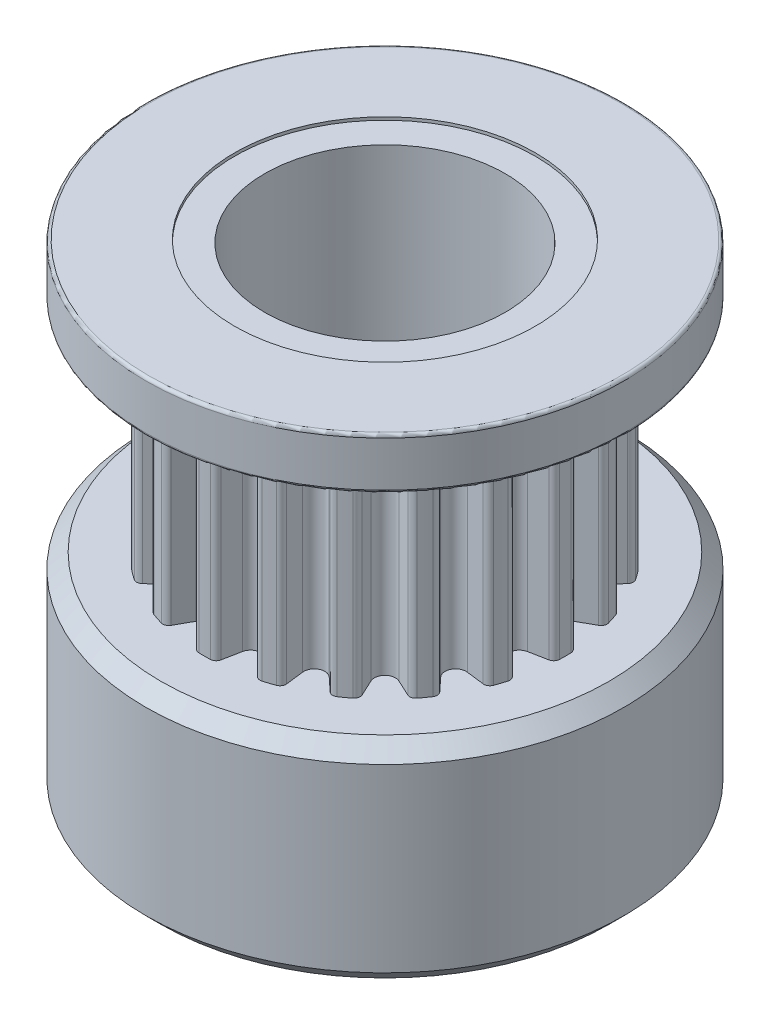
SolidWorks part; units mm, degrees
material "AISI 304"
ref_plane "Front Plane" through (0, 0, 0) normal (0, 0, 1) x (1, 0, 0)
ref_plane "Top Plane" through (0, 0, 0) normal (0, 1, 0) x (1, 0, 0)
ref_plane "Right Plane" through (0, 0, 0) normal (1, 0, 0) x (0, 0, -1)
sketch "Sketch1" plane through (0, 0, 0) normal (0, 1, 0) x (1, 0, 0)
  circle A0 centre (0, 0) radius 7.95
  dimension "D1" = 15.9
extrude "Boss-Extrude1" add sketch "Sketch1" along normal blind 7
sketch "Sketch2" plane through (0, 7, 0) normal (0, 1, 0) x (1, 0, 0)
  line L0 (0, 8.8295) -> (0, -9.5305) construction
  line L1 (-12.1222, 0) -> (11.146, 0) construction
  line L2 (-0.3802, 5.8356) -> (-0.4971, 5.2396)
  line L3 (0.3802, 5.8356) -> (0.4971, 5.2396)
  line L4 (2.1649, 5.4324) -> (2.0919, 4.8296)
  line L5 (1.4417, 5.6674) -> (1.1464, 5.1368)
  line L6 (3.7377, 4.4976) -> (3.4819, 3.9468)
  line L7 (3.1224, 4.9446) -> (2.6776, 4.5311)
  line L8 (4.9446, 3.1224) -> (4.5311, 2.6776)
  line L9 (4.4976, 3.7377) -> (3.9468, 3.4819)
  line L10 (5.6674, 1.4417) -> (5.1368, 1.1464)
  line L11 (5.4324, 2.1649) -> (4.8296, 2.0919)
  line L12 (5.8356, -0.3802) -> (5.2396, -0.4971)
  line L13 (5.8356, 0.3802) -> (5.2396, 0.4971)
  line L14 (5.4324, -2.1649) -> (4.8296, -2.0919)
  line L15 (5.6674, -1.4417) -> (5.1368, -1.1464)
  line L16 (4.4976, -3.7377) -> (3.9468, -3.4819)
  line L17 (4.9446, -3.1224) -> (4.5311, -2.6776)
  line L18 (3.1224, -4.9446) -> (2.6776, -4.5311)
  line L19 (3.7377, -4.4976) -> (3.4819, -3.9468)
  line L20 (1.4417, -5.6674) -> (1.1464, -5.1368)
  line L21 (2.1649, -5.4324) -> (2.0919, -4.8296)
  line L22 (-0.3802, -5.8356) -> (-0.4971, -5.2396)
  line L23 (0.3802, -5.8356) -> (0.4971, -5.2396)
  line L24 (-2.1649, -5.4324) -> (-2.0919, -4.8296)
  line L25 (-1.4417, -5.6674) -> (-1.1464, -5.1368)
  line L26 (-3.7377, -4.4976) -> (-3.4819, -3.9468)
  line L27 (-3.1224, -4.9446) -> (-2.6776, -4.5311)
  line L28 (-4.9446, -3.1224) -> (-4.5311, -2.6776)
  line L29 (-4.4976, -3.7377) -> (-3.9468, -3.4819)
  line L30 (-5.6674, -1.4417) -> (-5.1368, -1.1464)
  line L31 (-5.4324, -2.1649) -> (-4.8296, -2.0919)
  line L32 (-5.8356, 0.3802) -> (-5.2396, 0.4971)
  line L33 (-5.8356, -0.3802) -> (-5.2396, -0.4971)
  line L34 (-5.4324, 2.1649) -> (-4.8296, 2.0919)
  line L35 (-5.6674, 1.4417) -> (-5.1368, 1.1464)
  line L36 (-4.4976, 3.7377) -> (-3.9468, 3.4819)
  line L37 (-4.9446, 3.1224) -> (-4.5311, 2.6776)
  line L38 (-3.1224, 4.9446) -> (-2.6776, 4.5311)
  line L39 (-3.7377, 4.4976) -> (-3.4819, 3.9468)
  line L40 (-1.4417, 5.6674) -> (-1.1464, 5.1368)
  line L41 (-2.1649, 5.4324) -> (-2.0919, 4.8296)
  arc A1 (-0.55, 4.9697) -> (0.55, 4.9697) centre (0, 0) ccw construction
  arc A2 (0.1903, 5.997) -> (-0.1903, 5.997) centre (0, 0) ccw
  arc A3 (0.3802, 5.8356) -> (0.1903, 5.997) centre (0.184, 5.7971) ccw
  arc A4 (-0.3802, 5.8356) -> (-0.1903, 5.997) centre (-0.184, 5.7971) cw
  arc A5 (1.4417, 5.6674) -> (1.6722, 5.7623) centre (1.6164, 5.5702) cw
  arc A6 (2.0342, 5.6447) -> (1.6722, 5.7623) centre (0, 0) ccw
  arc A7 (2.1649, 5.4324) -> (2.0342, 5.6447) centre (1.9664, 5.4565) ccw
  arc A8 (3.1224, 4.9446) -> (3.371, 4.9635) centre (3.2586, 4.7981) cw
  arc A9 (3.6789, 4.7398) -> (3.371, 4.9635) centre (0, 0) ccw
  arc A10 (3.7377, 4.4976) -> (3.6789, 4.7398) centre (3.5563, 4.5818) ccw
  arc A11 (4.4976, 3.7377) -> (4.7398, 3.6789) centre (4.5818, 3.5563) cw
  arc A12 (4.9635, 3.371) -> (4.7398, 3.6789) centre (0, 0) ccw
  arc A13 (4.9446, 3.1224) -> (4.9635, 3.371) centre (4.7981, 3.2586) ccw
  arc A14 (5.4324, 2.1649) -> (5.6447, 2.0342) centre (5.4565, 1.9664) cw
  arc A15 (5.7623, 1.6722) -> (5.6447, 2.0342) centre (0, 0) ccw
  arc A16 (5.6674, 1.4417) -> (5.7623, 1.6722) centre (5.5702, 1.6164) ccw
  arc A17 (5.8356, 0.3802) -> (5.997, 0.1903) centre (5.7971, 0.184) cw
  arc A18 (5.997, -0.1903) -> (5.997, 0.1903) centre (0, 0) ccw
  arc A19 (5.8356, -0.3802) -> (5.997, -0.1903) centre (5.7971, -0.184) ccw
  arc A20 (5.6674, -1.4417) -> (5.7623, -1.6722) centre (5.5702, -1.6164) cw
  arc A21 (5.6447, -2.0342) -> (5.7623, -1.6722) centre (0, 0) ccw
  arc A22 (5.4324, -2.1649) -> (5.6447, -2.0342) centre (5.4565, -1.9664) ccw
  arc A23 (4.9446, -3.1224) -> (4.9635, -3.371) centre (4.7981, -3.2586) cw
  arc A24 (4.7398, -3.6789) -> (4.9635, -3.371) centre (0, 0) ccw
  arc A25 (4.4976, -3.7377) -> (4.7398, -3.6789) centre (4.5818, -3.5563) ccw
  arc A26 (3.7377, -4.4976) -> (3.6789, -4.7398) centre (3.5563, -4.5818) cw
  arc A27 (3.371, -4.9635) -> (3.6789, -4.7398) centre (0, 0) ccw
  arc A28 (3.1224, -4.9446) -> (3.371, -4.9635) centre (3.2586, -4.7981) ccw
  arc A29 (2.1649, -5.4324) -> (2.0342, -5.6447) centre (1.9664, -5.4565) cw
  arc A30 (1.6722, -5.7623) -> (2.0342, -5.6447) centre (0, 0) ccw
  arc A31 (1.4417, -5.6674) -> (1.6722, -5.7623) centre (1.6164, -5.5702) ccw
  arc A32 (0.3802, -5.8356) -> (0.1903, -5.997) centre (0.184, -5.7971) cw
  arc A33 (-0.1903, -5.997) -> (0.1903, -5.997) centre (0, 0) ccw
  arc A34 (-0.3802, -5.8356) -> (-0.1903, -5.997) centre (-0.184, -5.7971) ccw
  arc A35 (-1.4417, -5.6674) -> (-1.6722, -5.7623) centre (-1.6164, -5.5702) cw
  arc A36 (-2.0342, -5.6447) -> (-1.6722, -5.7623) centre (0, 0) ccw
  arc A37 (-2.1649, -5.4324) -> (-2.0342, -5.6447) centre (-1.9664, -5.4565) ccw
  arc A38 (-3.1224, -4.9446) -> (-3.371, -4.9635) centre (-3.2586, -4.7981) cw
  arc A39 (-3.6789, -4.7398) -> (-3.371, -4.9635) centre (0, 0) ccw
  arc A40 (-3.7377, -4.4976) -> (-3.6789, -4.7398) centre (-3.5563, -4.5818) ccw
  arc A41 (-4.4976, -3.7377) -> (-4.7398, -3.6789) centre (-4.5818, -3.5563) cw
  arc A42 (-4.9635, -3.371) -> (-4.7398, -3.6789) centre (0, 0) ccw
  arc A43 (-4.9446, -3.1224) -> (-4.9635, -3.371) centre (-4.7981, -3.2586) ccw
  arc A44 (-5.4324, -2.1649) -> (-5.6447, -2.0342) centre (-5.4565, -1.9664) cw
  arc A45 (-5.7623, -1.6722) -> (-5.6447, -2.0342) centre (0, 0) ccw
  arc A46 (-5.6674, -1.4417) -> (-5.7623, -1.6722) centre (-5.5702, -1.6164) ccw
  arc A47 (-5.8356, -0.3802) -> (-5.997, -0.1903) centre (-5.7971, -0.184) cw
  arc A48 (-5.997, 0.1903) -> (-5.997, -0.1903) centre (0, 0) ccw
  arc A49 (-5.8356, 0.3802) -> (-5.997, 0.1903) centre (-5.7971, 0.184) ccw
  arc A50 (-5.6674, 1.4417) -> (-5.7623, 1.6722) centre (-5.5702, 1.6164) cw
  arc A51 (-5.6447, 2.0342) -> (-5.7623, 1.6722) centre (0, 0) ccw
  arc A52 (-5.4324, 2.1649) -> (-5.6447, 2.0342) centre (-5.4565, 1.9664) ccw
  arc A53 (-4.9446, 3.1224) -> (-4.9635, 3.371) centre (-4.7981, 3.2586) cw
  arc A54 (-4.7398, 3.6789) -> (-4.9635, 3.371) centre (0, 0) ccw
  arc A55 (-4.4976, 3.7377) -> (-4.7398, 3.6789) centre (-4.5818, 3.5563) ccw
  arc A56 (-3.7377, 4.4976) -> (-3.6789, 4.7398) centre (-3.5563, 4.5818) cw
  arc A57 (-3.371, 4.9635) -> (-3.6789, 4.7398) centre (0, 0) ccw
  arc A58 (-3.1224, 4.9446) -> (-3.371, 4.9635) centre (-3.2586, 4.7981) ccw
  arc A59 (-2.1649, 5.4324) -> (-2.0342, 5.6447) centre (-1.9664, 5.4565) cw
  arc A60 (-1.6722, 5.7623) -> (-2.0342, 5.6447) centre (0, 0) ccw
  arc A61 (-1.4417, 5.6674) -> (-1.6722, 5.7623) centre (-1.6164, 5.5702) ccw
  arc A62 (-2.0919, 4.8296) -> (-2.6776, 4.5311) centre (-2.4393, 4.7875) cw
  arc A63 (-1.1464, 5.1368) -> (-0.4971, 5.2396) centre (-0.8405, 5.3069) ccw
  arc A64 (0.4971, 5.2396) -> (1.1464, 5.1368) centre (0.8405, 5.3069) ccw
  arc A65 (2.0919, 4.8296) -> (2.6776, 4.5311) centre (2.4393, 4.7875) ccw
  arc A66 (3.4819, 3.9468) -> (3.9468, 3.4819) centre (3.7994, 3.7994) ccw
  arc A67 (4.5311, 2.6776) -> (4.8296, 2.0919) centre (4.7875, 2.4393) ccw
  arc A68 (5.1368, 1.1464) -> (5.2396, 0.4971) centre (5.3069, 0.8405) ccw
  arc A69 (5.2396, -0.4971) -> (5.1368, -1.1464) centre (5.3069, -0.8405) ccw
  arc A70 (4.5311, -2.6776) -> (4.8296, -2.0919) centre (4.7875, -2.4393) cw
  arc A71 (3.9468, -3.4819) -> (3.4819, -3.9468) centre (3.7994, -3.7994) ccw
  arc A72 (2.6776, -4.5311) -> (2.0919, -4.8296) centre (2.4393, -4.7875) ccw
  arc A73 (1.1464, -5.1368) -> (0.4971, -5.2396) centre (0.8405, -5.3069) ccw
  arc A74 (-0.4971, -5.2396) -> (-1.1464, -5.1368) centre (-0.8405, -5.3069) ccw
  arc A75 (-2.0919, -4.8296) -> (-2.6776, -4.5311) centre (-2.4393, -4.7875) ccw
  arc A76 (-3.4819, -3.9468) -> (-3.9468, -3.4819) centre (-3.7994, -3.7994) ccw
  arc A77 (-4.5311, -2.6776) -> (-4.8296, -2.0919) centre (-4.7875, -2.4393) ccw
  arc A78 (-5.1368, -1.1464) -> (-5.2396, -0.4971) centre (-5.3069, -0.8405) ccw
  arc A79 (-5.2396, 0.4971) -> (-5.1368, 1.1464) centre (-5.3069, 0.8405) ccw
  arc A80 (-4.8296, 2.0919) -> (-4.5311, 2.6776) centre (-4.7875, 2.4393) ccw
  arc A81 (-3.4819, 3.9468) -> (-3.9468, 3.4819) centre (-3.7994, 3.7994) cw
  point P13 (0.35, 5.9898)
  point P16 (-0.35, 5.9898)
  point P171 (0, 0)
  dimension "D1" = 6
  dimension "D2" = 10
  dimension "D5" = 0.2
  dimension "D7" = 0.35
  dimension "D4" = 0.35
  dimension "D3" = 0.35
  dimension "D6" = 20
extrude "Boss-Extrude2" add sketch "Sketch2" along normal blind 7.3
sketch "Sketch3" plane through (0, 14.3, 0) normal (0, 1, 0) x (1, 0, 0)
  circle A0 centre (0, 0) radius 7.95
  dimension "D1" = 15.9
extrude "Boss-Extrude3" add sketch "Sketch3" along normal blind 1.7
sketch "Sketch4" plane through (0, 16, 0) normal (0, 1, 0) x (1, 0, 0)
  circle A0 centre (0, 0) radius 4
  dimension "D1" = 8
extrude "Cut-Extrude1" cut sketch "Sketch4" against normal through all
sketch "Sketch5" plane through (0, 16, 0) normal (0, 1, 0) x (1, 0, 0)
  circle A0 centre (0, 0) radius 5
  dimension "D1" = 10
extrude "Cut-Extrude2" cut sketch "Sketch5" against normal blind 0.1
sketch "Sketch6" plane through (0, 0, 0) normal (0, 0, 1) x (1, 0, 0)
  line L0 (-7.95, 3.5) -> (7.95, 3.5) construction
  line L1 (-7.95, 7) -> (-7.95, 0) construction
  line L2 (7.95, 0) -> (7.95, 7) construction
  line L3 (0, 0) -> (0, 7) construction
  line L4 (7.95, 7) -> (-7.95, 7) construction
  circle A0 centre (0, 3.5) radius 1.65
  dimension "D1" = 3.3
extrude "Cut-Extrude3" cut sketch "Sketch6" against normal through all
cosmetic thread "Cosmetic Thread1" parameters "D2"=4
fillet "Fillet1" radius 0.1 2 edges at (0, 14.3, 7.95) (0, 16, 7.95)
chamfer "Chamfer1" distance 0.5 angle 45 2 edges at (0, 0, 7.95) (0, 7, 7.95)
